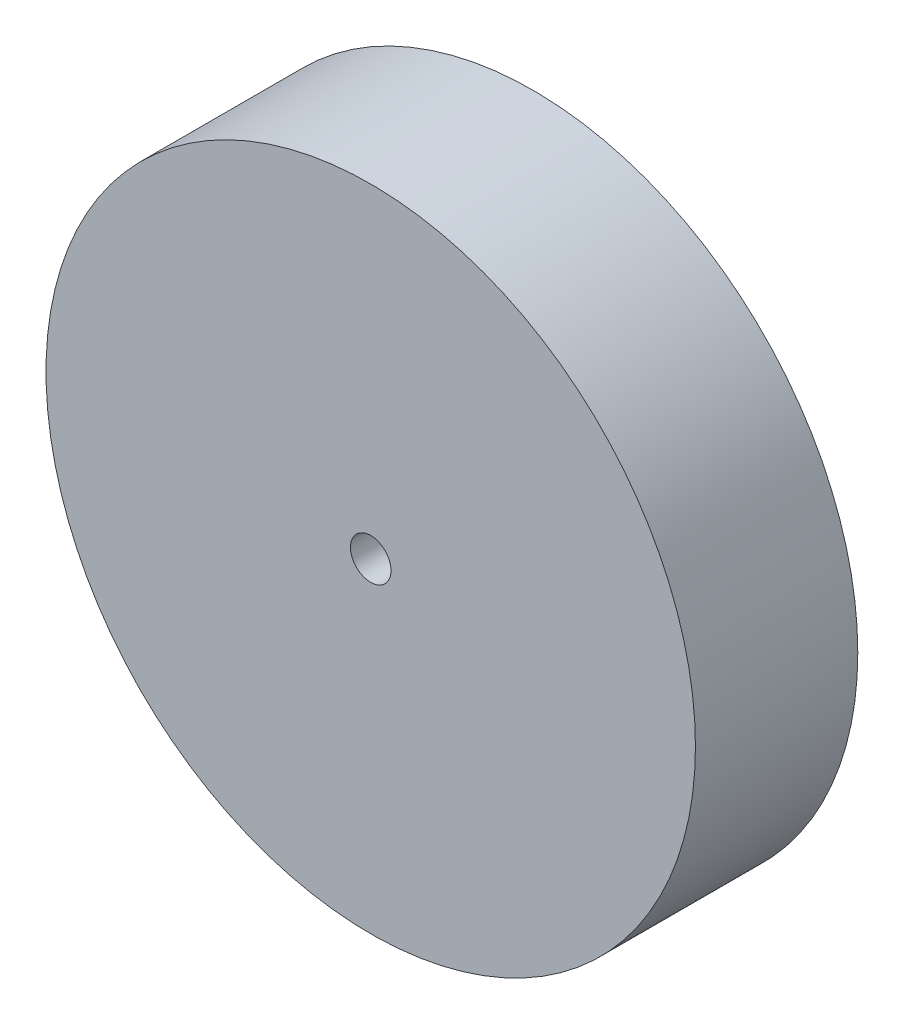
SolidWorks part; units mm, degrees
ref_plane "Front Plane" through (0, 0, 0) normal (0, 0, 1) x (1, 0, 0)
ref_plane "Top Plane" through (0, 0, 0) normal (0, 1, 0) x (1, 0, 0)
ref_plane "Right Plane" through (0, 0, 0) normal (1, 0, 0) x (0, 0, -1)
sketch "Sketch1" plane through (0, 0, 0) normal (0, 0, 1) x (1, 0, 0)
  circle A0 centre (0, 0) radius 63.5
  circle A1 centre (0, 0) radius 3.9688
  dimension "D1" = 127
  dimension "D2" = 7.9375
extrude "Boss-Extrude1" add sketch "Sketch1" along normal blind 31.75
